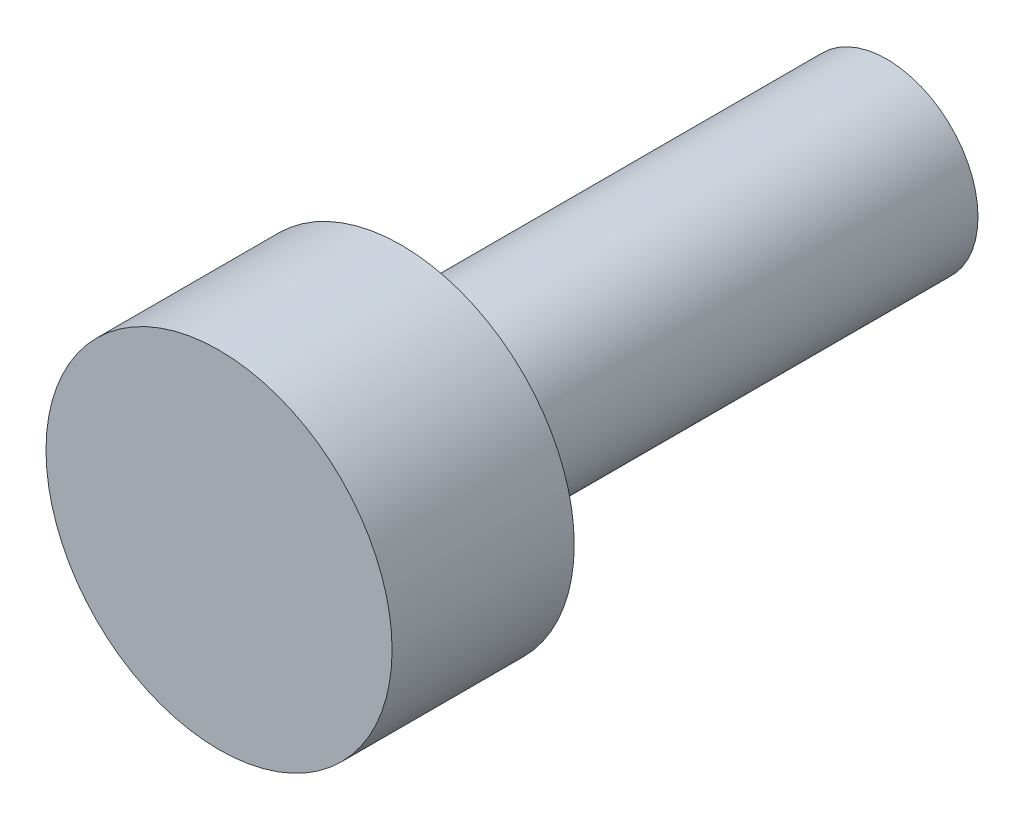
SolidWorks part; units mm, degrees
ref_plane "Front Plane" through (0, 0, 0) normal (0, 0, 1) x (1, 0, 0)
ref_plane "Top Plane" through (0, 0, 0) normal (0, 1, 0) x (1, 0, 0)
ref_plane "Right Plane" through (0, 0, 0) normal (1, 0, 0) x (0, 0, -1)
sketch "Sketch1" plane through (0, 0, 0) normal (0, 0, 1) x (1, 0, 0)
  circle A0 centre (0, 0) radius 1.5
  dimension "D1" = 3
extrude "Boss-Extrude1" add sketch "Sketch1" along normal blind 8
sketch "Sketch2" plane through (0, 0, 8) normal (0, 0, 1) x (1, 0, 0)
  circle A0 centre (0, 0) radius 2.85
  dimension "D1" = 5.7
extrude "Boss-Extrude2" add sketch "Sketch2" along normal blind 3
